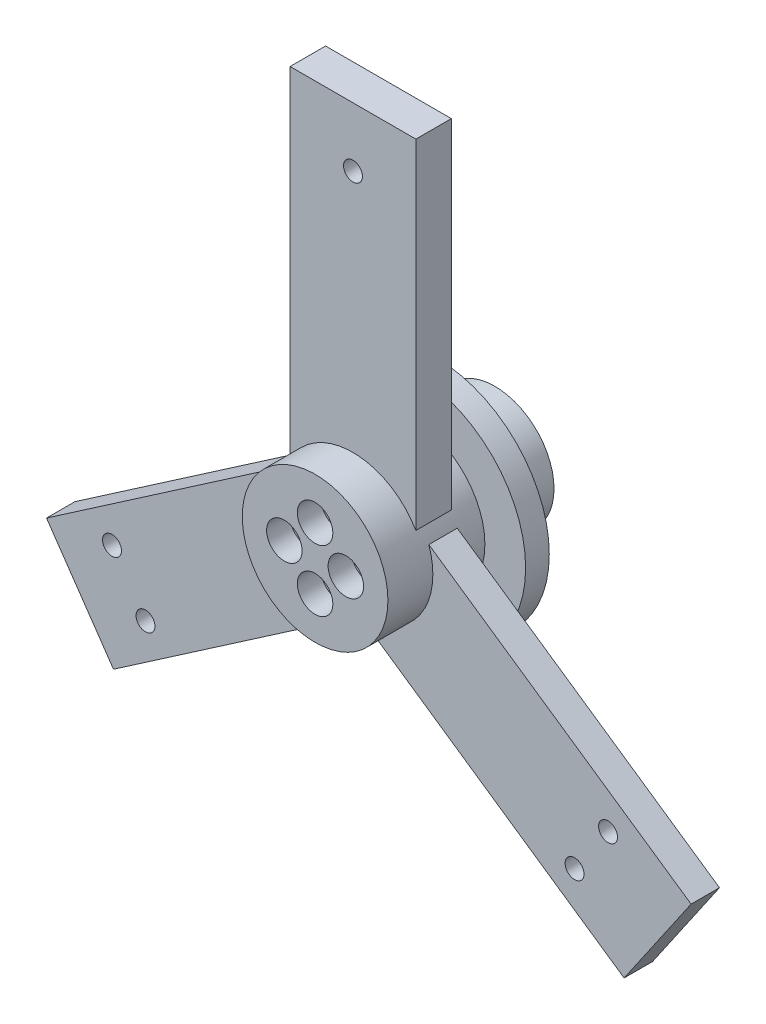
SolidWorks part; units mm, degrees
material "ABS"
ref_plane "Front Plane" through (0, 0, 0) normal (0, 0, 1) x (1, 0, 0)
ref_plane "Top Plane" through (0, 0, 0) normal (0, 1, 0) x (1, 0, 0)
ref_plane "Right Plane" through (0, 0, 0) normal (1, 0, 0) x (0, 0, -1)
sketch "Sketch1" plane through (0, 0, 0) normal (0, 0, 1) x (1, 0, 0)
  circle A0 centre (0, 0) radius 25
  dimension "D1" = 50
extrude "Boss-Extrude1" add sketch "Sketch1" along normal blind 25
sketch "Sketch2" plane through (0, 0, 25) normal (0, 0, 1) x (1, 0, 0)
  circle A0 centre (0, 0) radius 48
  dimension "D1" = 96
extrude "Boss-Extrude2" add sketch "Sketch2" along normal blind 10
sketch "Sketch3" plane through (0, 0, 35) normal (0, 0, 1) x (1, 0, 0)
  circle A0 centre (0, 0) radius 30.7858
extrude "Boss-Extrude3" add sketch "Sketch3" along normal blind 41
sketch "Sketch4" plane through (0, 0, 76) normal (0, 0, 1) x (1, 0, 0)
  line L0 (0, 0) -> (-64.4747, -44.3122)
  line L1 (0, 0) -> (69.196, -47.5571)
  line L2 (0, 0) -> (0, -64.1396)
  dimension "D1" = 111
  dimension "D2" = 55.5
  dimension "D3" = 55.5
ref_plane "Plane1" through (-25.3714, -17.4372, 0) normal (-0.8241, -0.5664, 0) x (0, 0, 1)
sketch "Sketch5" plane through (-25.3714, -17.4372, 0) normal (-0.8241, -0.5664, 0) x (0, 0, 1)
  line L1 (76, 30.7858) -> (35, 30.7858) construction
  line L2 (45, 24.7858) -> (57, 24.7858)
  line L3 (45, 24.7858) -> (45, -25.2142)
  line L4 (45, -25.2142) -> (57, -25.2142)
  line L5 (57, 24.7858) -> (57, -25.2142)
  line L7 (35, -48) -> (35, 48) construction
  dimension "D1" = 50
  dimension "D2" = 6
  dimension "D3" = 10
  dimension "D4" = 12
extrude "Boss-Extrude4" add sketch "Sketch5" along normal blind 113 and the other way blind 31
ref_plane "Plane2" through (25.3714, -17.4372, 0) normal (0.8241, -0.5664, 0) x (0, 0, -1)
sketch "Sketch6" plane through (25.3714, -17.4372, 0) normal (0.8241, -0.5664, 0) x (0, 0, -1)
  line L1 (-35, 30.7858) -> (-76, 30.7858) construction
  line L2 (-45, 24.7858) -> (-57, 24.7858)
  line L3 (-45, 24.7858) -> (-45, -25.2142)
  line L4 (-45, -25.2142) -> (-57, -25.2142)
  line L5 (-57, 24.7858) -> (-57, -25.2142)
  line L9 (-45, -25.5264) -> (-45, -143.2715) construction
  dimension "D1" = 6
  dimension "D2" = 50
  dimension "D3" = 12
  dimension "D4" = 0
extrude "Boss-Extrude5" add sketch "Sketch6" along normal blind 122 and the other way blind 21
sketch "Sketch7" plane through (0, 0, 0) normal (0, 0, -1) x (-1, 0, 0)
  circle A0 centre (0, 0) radius 3
  dimension "D1" = 6
extrude "Cut-Extrude1" cut sketch "Sketch7" against normal blind 25
ref_plane "Plane4" through (0, 0, 0) normal (-1, 0, 0) x (0, -1, 0)
ref_plane "Plane6" through (0, 30.7858, 0) normal (0, 1, 0) x (1, 0, 0)
sketch "Sketch9" plane through (0, 30.7858, 0) normal (0, 1, 0) x (1, 0, 0)
  line L0 (29.0874, -45) -> (139.9536, -45) construction
  line L1 (-26.5601, -45) -> (26.5992, -45)
  line L2 (-26.5601, -45) -> (-26.5601, -60)
  line L3 (-26.5601, -60) -> (26.5992, -60)
  line L4 (26.5992, -45) -> (26.5992, -60)
  dimension "D1" = 0
  dimension "D2" = 15
extrude "Boss-Extrude6" add sketch "Sketch9" along normal blind 128 and the other way blind 16
sketch "Sketch8" plane through (0, 0, 76) normal (0, 0, 1) x (1, 0, 0)
  line L0 (0, 33.8643) -> (0, -33.8643) construction
  line L1 (0, 0) -> (0, -64.1396) construction
  circle A0 centre (-13, 0) radius 7.5
  circle A1 centre (13, 0) radius 7.5
  circle A2 centre (0, 13) radius 7.5
  circle A3 centre (0, -13) radius 7.5
  dimension "D1" = 15
  dimension "D2" = 15
  dimension "D3" = 13
  dimension "D5" = 15
  dimension "D6" = 15
  dimension "D7" = 13
  dimension "D8" = 13
  dimension "D4" = 13
extrude "Cut-Extrude2" cut sketch "Sketch8" against normal blind 10
sketch "Sketch10" plane through (0, 0, 57) normal (0, 0, 1) x (1, 0, 0)
  line L0 (-104.2161, -102.2209) -> (-132.5364, -61.0146) construction
  line L1 (-0.2756, -30.7845) -> (-104.2161, -102.2209) construction
  line L2 (-29.0874, 10.084) -> (-132.5364, -61.0146) construction
  circle A0 centre (-104.8532, -57.156) radius 4
  circle A1 centre (-90.693, -77.7591) radius 4
  dimension "D1" = 8
  dimension "D2" = 8
  dimension "D3" = 25
  dimension "D4" = 25
  dimension "D5" = 12.5
  dimension "D6" = 12.5
extrude "Cut-Extrude3" cut sketch "Sketch10" against normal blind 72
mirror "Mirror1" about plane through (0, 0, 0) normal (-1, 0, 0) of "Cut-Extrude3"
sketch "Sketch11" plane through (0, 0, 60) normal (0, 0, 1) x (1, 0, 0)
  line L2 (-26.5601, 158.7858) -> (26.5992, 158.7858) construction
  circle A0 centre (0.0196, 133.7858) radius 4
  point P4 (0.0196, 158.7858)
  dimension "D1" = 25
  dimension "D2" = 8
extrude "Cut-Extrude4" cut sketch "Sketch11" against normal blind 72
